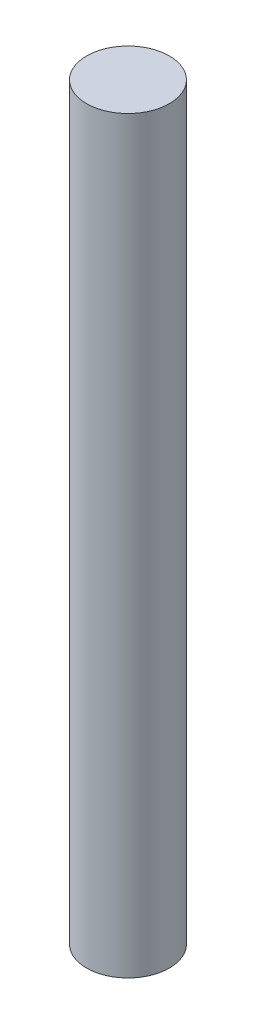
SolidWorks part; units mm, degrees
ref_plane "Front Plane" through (0, 0, 0) normal (0, 0, 1) x (1, 0, 0)
ref_plane "Top Plane" through (0, 0, 0) normal (0, 1, 0) x (1, 0, 0)
ref_plane "Right Plane" through (0, 0, 0) normal (1, 0, 0) x (0, 0, -1)
sketch "Sketch1" plane through (0, 0, 0) normal (0, 1, 0) x (1, 0, 0)
  circle A0 centre (0, 0) radius 10.5
  dimension "D1" = 21
extrude "Boss-Extrude1" add sketch "Sketch1" along normal blind 190
